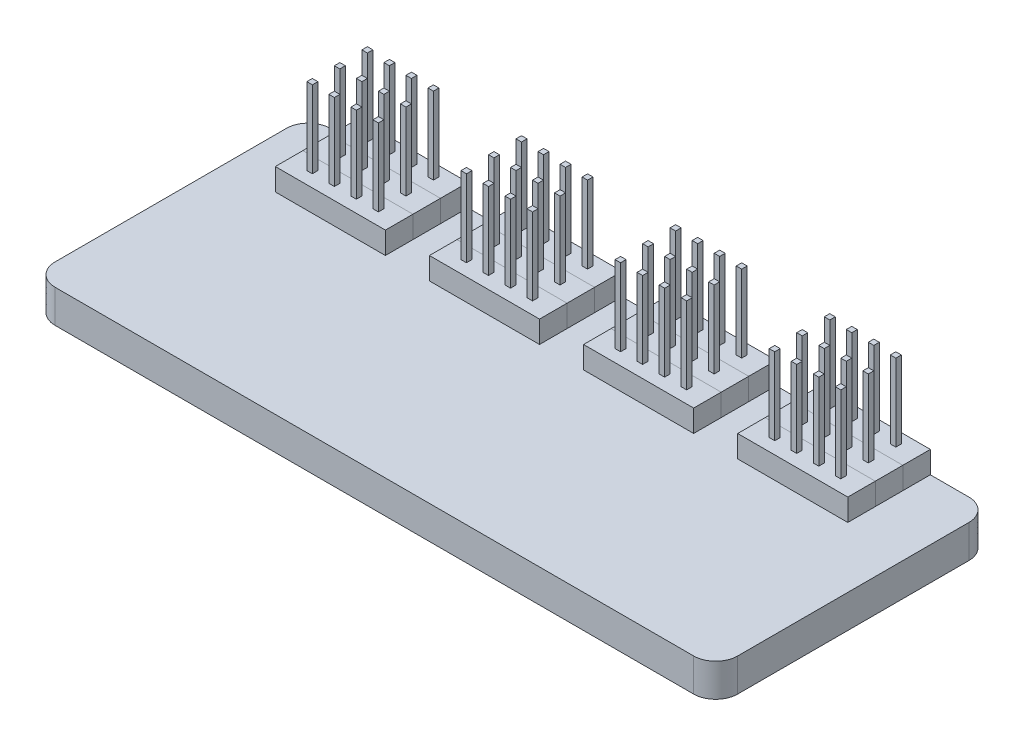
SolidWorks part; units mm, degrees
ref_plane "정면" through (0, 0, 0) normal (0, 0, 1) x (1, 0, 0)
ref_plane "윗면" through (0, 0, 0) normal (0, 1, 0) x (1, 0, 0)
ref_plane "우측면" through (0, 0, 0) normal (1, 0, 0) x (0, 0, -1)
sketch "스케치1" plane through (0, 0, 0) normal (0, 1, 0) x (1, 0, 0)
  line L0 (-29, -12.5) -> (29, -12.5)
  line L1 (-31, 10.5) -> (-31, -10.5)
  line L2 (-25.3, 12.5) -> (-29, 12.5)
  line L3 (-23.2, 12.5) -> (-25.3, 12.5)
  line L4 (-22.8, 12.5) -> (-23.2, 12.5)
  line L5 (-20.7, 12.5) -> (-22.8, 12.5)
  line L6 (-20.3, 12.5) -> (-20.7, 12.5)
  line L7 (-18.2, 12.5) -> (-20.3, 12.5)
  line L8 (-17.8, 12.5) -> (-18.2, 12.5)
  line L9 (-15.7, 12.5) -> (-17.8, 12.5)
  line L10 (-12.8, 12.5) -> (-15.7, 12.5)
  line L11 (-10.7, 12.5) -> (-12.8, 12.5)
  line L12 (-10.3, 12.5) -> (-10.7, 12.5)
  line L13 (-8.2, 12.5) -> (-10.3, 12.5)
  line L14 (-7.8, 12.5) -> (-8.2, 12.5)
  line L15 (-5.7, 12.5) -> (-7.8, 12.5)
  line L16 (-5.3, 12.5) -> (-5.7, 12.5)
  line L17 (-3.2, 12.5) -> (-5.3, 12.5)
  line L18 (3.2, 12.5) -> (-3.2, 12.5)
  line L19 (5.3, 12.5) -> (3.2, 12.5)
  line L20 (5.7, 12.5) -> (5.3, 12.5)
  line L21 (7.8, 12.5) -> (5.7, 12.5)
  line L22 (8.2, 12.5) -> (7.8, 12.5)
  line L23 (10.3, 12.5) -> (8.2, 12.5)
  line L24 (10.7, 12.5) -> (10.3, 12.5)
  line L25 (12.8, 12.5) -> (10.7, 12.5)
  line L26 (15.7, 12.5) -> (12.8, 12.5)
  line L27 (17.8, 12.5) -> (15.7, 12.5)
  line L28 (18.2, 12.5) -> (17.8, 12.5)
  line L29 (20.3, 12.5) -> (18.2, 12.5)
  line L30 (20.7, 12.5) -> (20.3, 12.5)
  line L31 (22.8, 12.5) -> (20.7, 12.5)
  line L32 (23.2, 12.5) -> (22.8, 12.5)
  line L33 (25.3, 12.5) -> (23.2, 12.5)
  line L34 (29, 12.5) -> (25.3, 12.5)
  line L35 (31, -10.5) -> (31, 10.5)
  spline S0 degree 3 poles (-31, -10.5) (-30.9982, -10.5655) (-30.9945, -10.6964) (-30.9645, -10.8908) (-30.9171, -11.0815) (-30.8287, -11.3281) (-30.6737, -11.6184) (-30.4233, -11.9233) (-30.1184, -12.1737) (-29.8281, -12.3287) (-29.5815, -12.417) (-29.4119, -12.4595) (-29.2612, -12.4842) (-29.1309, -12.4975) (-29.0437, -12.4992) (-29, -12.5) knots 0 0 0 0 0.062536 0.125072 0.187608 0.250144 0.375065 0.499986 0.624907 0.749828 0.812364 0.8749 0.91663 0.95827 1 1 1 1
  spline S1 degree 3 poles (-29, 12.5) (-29.0655, 12.4982) (-29.1964, 12.4945) (-29.3908, 12.4645) (-29.5815, 12.4171) (-29.8281, 12.3287) (-30.1184, 12.1737) (-30.4233, 11.9233) (-30.6737, 11.6184) (-30.8287, 11.3281) (-30.917, 11.0815) (-30.9595, 10.9119) (-30.9842, 10.7612) (-30.9975, 10.6309) (-30.9992, 10.5437) (-31, 10.5) knots 0 0 0 0 0.062536 0.125072 0.187608 0.250144 0.375065 0.499986 0.624907 0.749828 0.812364 0.8749 0.91663 0.95827 1 1 1 1
  spline S2 degree 3 poles (31, 10.5) (30.9982, 10.5655) (30.9945, 10.6964) (30.9645, 10.8908) (30.9171, 11.0815) (30.8287, 11.3281) (30.6737, 11.6184) (30.4233, 11.9233) (30.1184, 12.1737) (29.8281, 12.3287) (29.5815, 12.417) (29.4119, 12.4595) (29.2612, 12.4842) (29.1309, 12.4975) (29.0437, 12.4992) (29, 12.5) knots 0 0 0 0 0.062536 0.125072 0.187608 0.250144 0.375065 0.499986 0.624907 0.749828 0.812364 0.8749 0.91663 0.95827 1 1 1 1
  spline S3 degree 3 poles (29, -12.5) (29.0655, -12.4982) (29.1964, -12.4945) (29.3908, -12.4645) (29.5815, -12.4171) (29.8281, -12.3287) (30.1184, -12.1737) (30.4233, -11.9233) (30.6737, -11.6184) (30.8287, -11.3281) (30.917, -11.0815) (30.9595, -10.9119) (30.9842, -10.7612) (30.9975, -10.6309) (30.9992, -10.5437) (31, -10.5) knots 0 0 0 0 0.062536 0.125072 0.187608 0.250144 0.375065 0.499986 0.624907 0.749828 0.812364 0.8749 0.91663 0.95827 1 1 1 1
extrude "보스-돌출1" add sketch "스케치1" along normal blind 3
sketch "스케치3" plane through (0, 3, 0) normal (0, 1, 0) x (1, 0, 0)
  line L0 (31, -10.5) -> (31, 10.5) construction
  line L1 (15.5, 10) -> (25.5, 10)
  line L2 (15.5, 10) -> (15.5, 12.5)
  line L3 (15.5, 12.5) -> (25.5, 12.5)
  line L4 (25.5, 10) -> (25.5, 12.5)
  line L5 (29, 12.5) -> (-29, 12.5) construction
  dimension "D1" = 10
  dimension "D2" = 2.5
  dimension "D3" = 5.5
extrude "보스-돌출2" add sketch "스케치3" along normal blind 2 separate body
sketch "스케치4" plane through (0, 5, 0) normal (0, 1, 0) x (1, 0, 0)
  line L0 (19.2533, 11.6104) -> (19.7533, 11.6104)
  line L1 (17.2533, 11.6104) -> (17.7533, 11.6104)
  line L2 (17.2533, 11.6104) -> (17.2533, 11.1104)
  line L3 (17.2533, 11.1104) -> (17.7533, 11.1104)
  line L4 (17.7533, 11.6104) -> (17.7533, 11.1104)
  line L5 (19.2533, 11.6104) -> (19.2533, 11.1104)
  line L6 (19.2533, 11.1104) -> (19.7533, 11.1104)
  line L7 (19.7533, 11.6104) -> (19.7533, 11.1104)
  line L8 (21.2533, 11.6104) -> (21.7533, 11.6104)
  line L9 (21.2533, 11.6104) -> (21.2533, 11.1104)
  line L10 (21.2533, 11.1104) -> (21.7533, 11.1104)
  line L11 (21.7533, 11.6104) -> (21.7533, 11.1104)
  line L12 (23.2533, 11.6104) -> (23.7533, 11.6104)
  line L13 (23.2533, 11.6104) -> (23.2533, 11.1104)
  line L14 (23.2533, 11.1104) -> (23.7533, 11.1104)
  line L15 (23.7533, 11.6104) -> (23.7533, 11.1104)
  dimension "D1" = 0.5
  dimension "D2" = 0.5
  dimension "D3" = 4
extrude "보스-돌출3" add sketch "스케치4" along normal blind 7 separate body
pattern_linear "선형 패턴1" count 4 spacing 14 along (-1, 0, 0) count 3 spacing 2.5 along (0, 0, 1) of bodies 106 105 104 103 102
